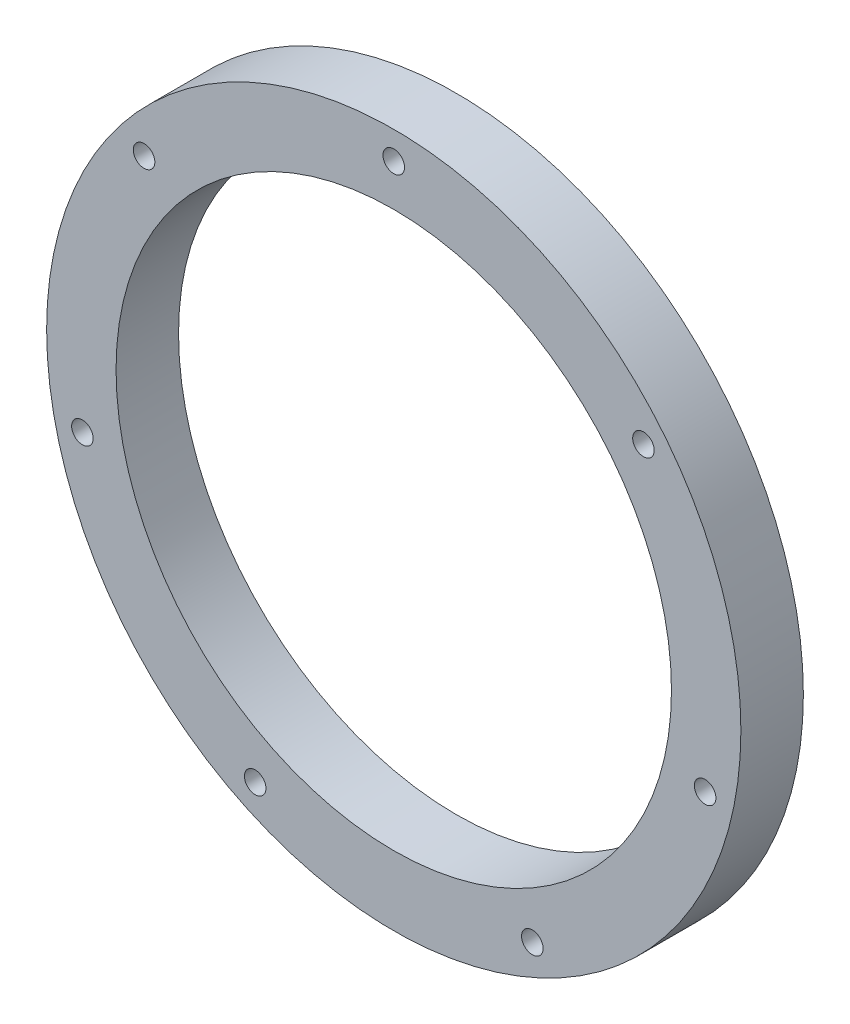
SolidWorks part; units mm, degrees
ref_plane "Ebene vorne" through (0, 0, 0) normal (0, 0, 1) x (1, 0, 0)
ref_plane "Ebene oben" through (0, 0, 0) normal (0, 1, 0) x (1, 0, 0)
ref_plane "Ebene rechts" through (0, 0, 0) normal (1, 0, 0) x (0, 0, -1)
sketch "Skizze1" plane through (0, 0, 0) normal (0, 0, 1) x (1, 0, 0)
  line L0 (0, 0) -> (-48526.5407, 0) construction
  line L2 (0, 0) -> (0, -48526.5407) construction
  circle A0 centre (0, 0) radius 40
  circle A1 centre (0, 0) radius 50
  dimension "D1" = 100
  dimension "D2" = 80
extrude "Aufsatz-Linear austragen1" add sketch "Skizze1" along normal blind 9
hole_wizard "Ø3.1 (3.1) Durchmesser Bohrung1" positions "Skizze2" profile "Skizze3" hole size "Ø3.1" standard "ISO"
sketch "Skizze2" plane through (0, 0, 9) normal (0, 0, 1) x (1, 0, 0)
  line L0 (0, 0) -> (0, 50000) construction
  circle A0 centre (0, 0) radius 46 construction
  circle A1 centre (0, 0) radius 46 construction
  circle A2 centre (0, 0) radius 46 construction
  circle A3 centre (0, 0) radius 46 construction
  circle A4 centre (0, 0) radius 46 construction
  circle A5 centre (0, 0) radius 46 construction
  point P10 (0, 46)
  point P28 (-39.8372, 23) [skipped]
  point P30 (-39.8372, -23) [skipped]
  point P32 (0, -46) [skipped]
  point P34 (39.8372, -23) [skipped]
  point P36 (39.8372, 23) [skipped]
  dimension "D1" = 92
  dimension "D2" = 6
sketch "Skizze3" plane through (0, 46, 9) normal (1, 0, 0) x (0, -1, 0)
  line L0 (0, 0) -> (0, 9)
  line L1 (0, 9) -> (1.55, 9)
  line L2 (1.55, 9) -> (1.55, 0)
  line L5 (1.55, 0) -> (0, 0)
  line L11 (0, -6.35) -> (0, 107.95) construction
  dimension "Bohrerdurchmesser" = 3.1
  dimension "Bohrungstiefe" = 9
pattern_circular "Kreismuster1" count 7 over 360 about axis through (0, 0, 0) along (0, 0, 1) of "Ø3.1 (3.1) Durchmesser Bohrung1"
sketch "Skizze4" plane through (0, 0, 0) normal (0, 0, 1) x (1, 0, 0)
  circle A0 centre (0, 46) radius 3.1
  dimension "D1" = 6.2
extrude "Schnitt-Linear austragen1" cut sketch "Skizze4" along normal blind 3.3
pattern_circular "Kreismuster2" count 7 over 360 about axis through (0, 0, 0) along (0, 0, 1) of "Schnitt-Linear austragen1"
